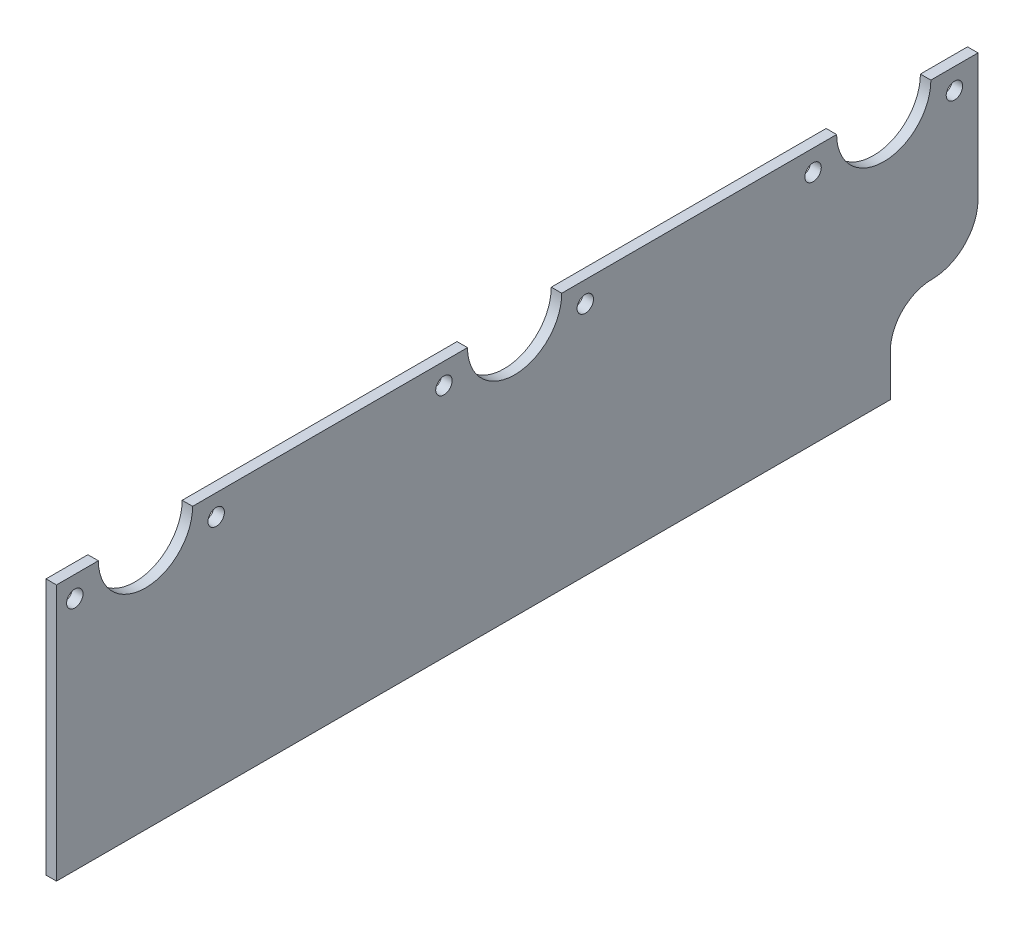
SolidWorks part; units mm, degrees
material "6061 Alloy"
ref_plane "Front Plane" through (0, 0, 0) normal (0, 0, 1) x (1, 0, 0)
ref_plane "Top Plane" through (0, 0, 0) normal (0, 1, 0) x (1, 0, 0)
ref_plane "Right Plane" through (0, 0, 0) normal (1, 0, 0) x (0, 0, -1)
sketch "Sketch1" plane through (0, 0, 0) normal (1, 0, 0) x (0, 0, -1)
  line L0 (139.7, 0) -> (-139.7, 0)
  line L1 (-139.7, 0) -> (-139.7, 77.7875)
  line L2 (-139.7, 77.7875) -> (-127, 77.7875)
  line L3 (-98.425, 77.7875) -> (-15.0812, 77.7875)
  line L4 (13.4938, 77.7875) -> (96.8375, 77.7875)
  line L5 (125.4125, 77.7875) -> (139.7, 77.7875)
  line L6 (139.7, 77.7875) -> (139.7, 0)
  line L7 (-139.7, 25.4) -> (139.7, 25.4) construction
  arc A6 (-127, 77.7875) -> (-98.425, 77.7875) centre (-112.7125, 77.7875) ccw
  arc A7 (-15.0812, 77.7875) -> (13.4938, 77.7875) centre (-0.7937, 77.7875) ccw
  arc A8 (96.8375, 77.7875) -> (125.4125, 77.7875) centre (111.125, 77.7875) ccw
  point P4 (0, 0)
  dimension "D1" = 25.4
  dimension "D3" = 14.2875
  dimension "D5" = 28.575
  dimension "D6" = 38.1
  dimension "D2" = 279.4
  dimension "D4" = 12.7
extrude "Boss-Extrude1" add sketch "Sketch1" along normal blind 3.175
hole_wizard "#10 Clearance Hole1" positions "Sketch2" profile "Sketch3" hole size "#10" standard "ANSI Inch" end condition through all
sketch "Sketch2" plane through (3.175, 0, 0) normal (1, 0, 0) x (0, 0, -1)
  line L0 (-134.1437, 71.4375) -> (-91.2812, 71.4375) construction
  line L2 (-22.225, 71.4375) -> (20.6375, 71.4375) construction
  line L4 (89.6938, 71.4375) -> (132.5563, 71.4375) construction
  line L6 (-127, 77.7875) -> (-139.7, 77.7875) construction
  line L7 (-112.7125, 71.4375) -> (-112.7125, 77.7875) construction
  line L9 (-0.7937, 77.7875) -> (-0.7937, 71.4375) construction
  line L11 (111.125, 77.7875) -> (111.125, 71.4375) construction
  point P0 (-134.1437, 71.4375)
  point P2 (-91.2812, 71.4375)
  point P4 (-22.225, 71.4375)
  point P6 (20.6375, 71.4375)
  point P8 (89.6938, 71.4375)
  point P10 (132.5563, 71.4375)
  dimension "D1" = 42.8625
  dimension "D2" = 6.35
sketch "Sketch3" plane through (3.175, 71.4375, 134.1437) normal (0, 1, 0) x (0, 0, -1)
  line L0 (0, 0) -> (0, 3.175)
  line L1 (0, 3.175) -> (2.4892, 3.175)
  line L2 (2.4892, 3.175) -> (2.4892, 0)
  line L5 (2.4892, 0) -> (0, 0)
  line L11 (0, -6.35) -> (0, 107.95) construction
  dimension "Thru Hole Dia." = 4.9784
  dimension "Thru Hole Depth" = 3.175
sketch "Sketch4" plane through (0, 0, 0) normal (-1, 0, 0) x (0, 0, 1)
  line L1 (-113.3729, 12.7) -> (-113.3729, 0) construction
  line L2 (139.7, 0) -> (-139.7, 0) construction
  line L3 (-139.7, 25.4) -> (-132.2754, 25.4) construction
  line L4 (-139.7, 0) -> (-139.7, 77.7875) construction
  line L5 (-125.73, 25.0571) -> (-132.2754, 25.4) construction
  line L6 (-139.7, 25.4) -> (-139.7, 0) construction
  line L7 (-139.7, 0) -> (-113.3729, 0) construction
  line L10 (-113.1189, 12.7) -> (-113.1189, 0)
  line L13 (-125.7233, 25.3111) -> (-132.2688, 25.654) construction
  line L14 (-139.954, 25.654) -> (-132.2688, 25.654) construction
  line L15 (-139.954, 25.654) -> (-139.954, -0.254) construction
  line L16 (-139.954, -0.254) -> (-113.1189, -0.254) construction
  line L17 (-139.7, 38.8937) -> (-139.7, 0)
  line L18 (-139.7, 0) -> (-113.1189, 0)
  line L20 (-113.1189, 12.7) -> (-113.1189, -0.254) construction
  arc A1 (-132.2754, 25.4) -> (-132.2754, 0) centre (-125.73, 12.7) ccw construction
  circle A2 centre (-125.73, 12.7) radius 12.3571 construction
  arc A3 (-132.2754, 25.4) -> (-132.2754, 0) centre (-125.73, 12.7) ccw construction
  arc A4 (-113.3729, 12.7) -> (-125.73, 25.0571) centre (-125.73, 12.7) ccw construction
  arc A5 (-113.1189, 12.7) -> (-125.7233, 25.3111) centre (-125.73, 12.7) ccw
  arc A6 (-125.7233, 25.3111) -> (-139.7, 38.8937) centre (-125.7159, 39.3011) cw
  dimension "D1" = 0.254
extrude "Cut-Extrude1" cut sketch "Sketch4" against normal through all
